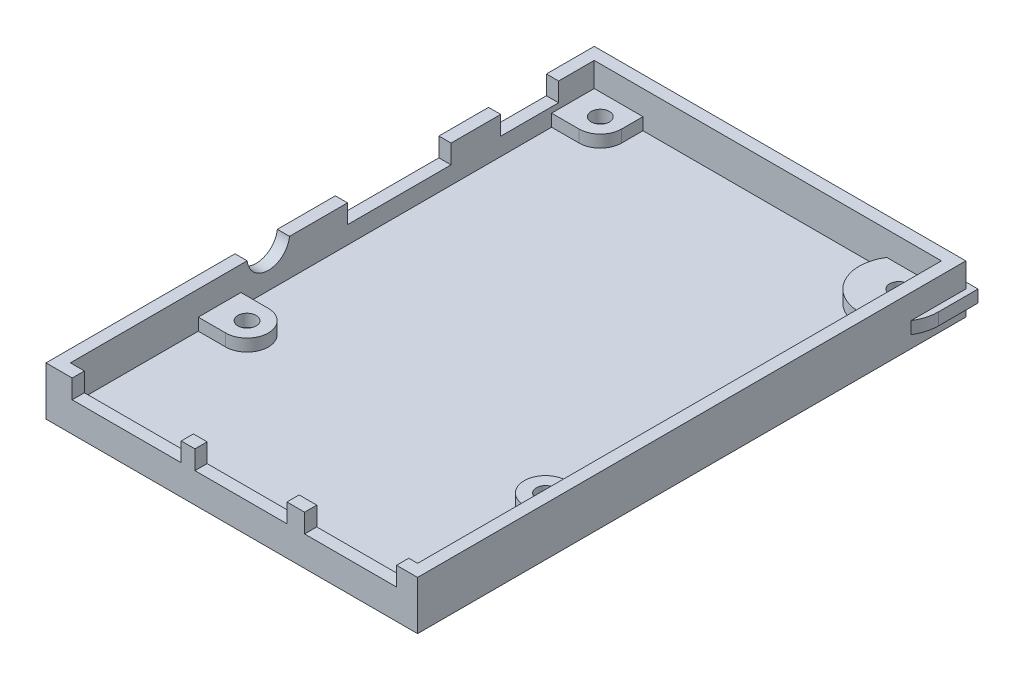
SolidWorks part; units mm, degrees
material "Acrylic (Medium-high impact)"
ref_plane "Front Plane" through (0, 0, 0) normal (0, 0, 1) x (1, 0, 0)
ref_plane "Top Plane" through (0, 0, 0) normal (0, 1, 0) x (1, 0, 0)
ref_plane "Right Plane" through (0, 0, 0) normal (1, 0, 0) x (0, 0, -1)
sketch "Sketch1" plane through (0, 0, 0) normal (0, 1, 0) x (1, 0, 0)
  line L1 (-30.5, -45) -> (30.5, -45)
  line L2 (-30.5, -45) -> (-30.5, 45)
  line L3 (-30.5, 45) -> (30.5, 45)
  line L4 (30.5, -45) -> (30.5, 45)
  line L5 (-30.5, -45) -> (30.5, 45) construction
  line L6 (-30.5, 45) -> (30.5, -45) construction
  point P0 (0, 0)
  dimension "D1" = 90
  dimension "D2" = 61
extrude "Boss-Extrude1" add sketch "Sketch1" along normal blind 8
ref_plane "Plane1" through (0, 2, 0) normal (0, 1, 0) x (1, 0, 0)
sketch "Sketch4" plane through (0, 2, 0) normal (0, 1, 0) x (1, 0, 0)
  line L0 (30.5, -45) -> (30.5, 45) construction
  line L1 (-28.5, -43) -> (28.5, -43)
  line L2 (-28.5, -43) -> (-28.5, 43)
  line L3 (-28.5, 43) -> (28.5, 43)
  line L4 (28.5, -43) -> (28.5, 43)
  line L5 (-28.5, -43) -> (28.5, 43) construction
  line L6 (-28.5, 43) -> (28.5, -43) construction
  line L7 (30.5, 45) -> (-30.5, 45) construction
  point P0 (0, 0)
  dimension "D1" = 2
  dimension "D2" = 2
extrude "Cut-Extrude1" cut sketch "Sketch4" along normal up to surface (6 mm away) up to face at (0, 8, 0)
sketch "Sketch5" plane through (0, 2, 0) normal (0, 1, 0) x (1, 0, 0)
  line L0 (28.5, 43) -> (28.5, -43) construction
  line L1 (25, -15) -> (28.5, -15)
  line L2 (-28.5, 43) -> (28.5, 43) construction
  line L3 (28.5, -43) -> (28.5, 43) construction
  line L4 (25, -22) -> (28.5, -22)
  line L5 (28.5, -22) -> (28.5, -15)
  line L9 (31.5, 39.5) -> (31.5, 46)
  line L10 (31.5, 46) -> (25, 46)
  line L12 (28.5, 43) -> (-28.5, 43) construction
  line L13 (-20.5, 39.5) -> (-20.5, 43)
  line L15 (-24, 36) -> (-28.5, 36)
  line L16 (-28.5, 43) -> (-28.5, -43) construction
  line L17 (-28.5, 36) -> (-28.5, 43)
  line L18 (-20.5, 43) -> (-28.5, 43)
  line L19 (-24, -15) -> (-28.5065, -15)
  line L22 (-28.5065, -15) -> (-28.5, -22)
  line L23 (-28.5, -43) -> (-28.5, 43) construction
  line L24 (-28.5, -22) -> (-24, -22)
  circle A0 centre (25, 39.5) radius 1.5
  circle A1 centre (-24, 39.5) radius 1.5
  circle A2 centre (25, -18.5) radius 1.5
  circle A3 centre (-24, -18.5) radius 1.5
  arc A4 (-24, -22) -> (-24, -15) centre (-24, -18.5) ccw
  arc A5 (25, -15) -> (25, -22) centre (25, -18.5) ccw
  arc A6 (25, 46) -> (31.5, 39.5) centre (25, 39.5) ccw
  arc A7 (-24, 36) -> (-20.5, 39.5) centre (-24, 39.5) ccw
  point P4 (-28.5, -14.7585)
  dimension "D1" = 3
  dimension "D5" = 3
  dimension "D7" = 3
  dimension "D8" = 7
  dimension "D9" = 7
  dimension "D2" = 49
  dimension "D3" = 3.5
  dimension "D4" = 3.5
  dimension "D6" = 58
extrude "Boss-Extrude12" add sketch "Sketch5" along normal blind 2
sketch "Sketch6" plane through (-30.5, 0, 0) normal (-1, 0, 0) x (0, 0, 1)
  line L0 (15, 4) -> (22, 4) construction
  line L1 (-43, 8) -> (-43, 4) construction
  line L3 (-19.5, 4.9) -> (-2.5, 4.9)
  line L4 (-19.5, 4.9) -> (-19.5, 11.4)
  line L5 (-19.5, 11.4) -> (-2.5, 11.4)
  line L6 (-2.5, 4.9) -> (-2.5, 11.4)
  line L7 (-19.5, 4.9) -> (-2.5, 11.4) construction
  line L8 (-19.5, 11.4) -> (-2.5, 4.9) construction
  line L10 (-37.15, 4.9) -> (-27.65, 4.9)
  line L11 (-37.15, 4.9) -> (-37.15, 8.9)
  line L12 (-37.15, 8.9) -> (-27.65, 8.9)
  line L13 (-27.65, 4.9) -> (-27.65, 8.9)
  line L14 (-37.15, 4.9) -> (-27.65, 8.9) construction
  line L15 (-37.15, 8.9) -> (-27.65, 4.9) construction
  circle A0 centre (10.5, 8.4) radius 3.5
  point P2 (0, 0)
  point P6 (-11, 8.15)
  point P11 (0, 0)
  point P12 (-19.5, 10.4247)
  point P13 (-32.4, 6.9)
  point P18 (0, 0)
  point P19 (0, 0)
  dimension "D1" = 7
  dimension "D2" = 4.4
  dimension "D3" = 53.5
  dimension "D4" = 17
  dimension "D5" = 9.5
  dimension "D6" = 10.6
  dimension "D7" = 32
  dimension "D9" = 6.5
  dimension "D10" = 4
extrude "Cut-Extrude2" cut sketch "Sketch6" against normal up to next
sketch "Sketch8" plane through (0, 0, 45) normal (0, 0, 1) x (1, 0, 0)
  line L0 (-28.5, 4) -> (-24, 4) construction
  line L1 (-26.2, 20.4) -> (-8.3, 20.4)
  line L2 (-26.2, 20.4) -> (-26.2, 4.9)
  line L3 (-26.2, 4.9) -> (-8.3, 4.9)
  line L4 (-8.3, 20.4) -> (-8.3, 4.9)
  line L5 (-26.2, 20.4) -> (-8.3, 4.9) construction
  line L6 (-26.2, 4.9) -> (-8.3, 20.4) construction
  line L7 (-6.05, 20.9) -> (9.05, 20.9)
  line L8 (-6.05, 20.9) -> (-6.05, 4.9)
  line L9 (-6.05, 4.9) -> (9.05, 4.9)
  line L10 (9.05, 20.9) -> (9.05, 4.9)
  line L11 (-6.05, 20.9) -> (9.05, 4.9) construction
  line L12 (-6.05, 4.9) -> (9.05, 20.9) construction
  line L13 (11.95, 20.9) -> (27.05, 20.9)
  line L14 (11.95, 20.9) -> (11.95, 4.9)
  line L15 (11.95, 4.9) -> (27.05, 4.9)
  line L16 (27.05, 20.9) -> (27.05, 4.9)
  line L17 (11.95, 20.9) -> (27.05, 4.9) construction
  line L18 (11.95, 4.9) -> (27.05, 20.9) construction
  line L20 (-28.5, 8) -> (-28.5, 2) construction
  point P0 (-17.25, 12.65)
  point P5 (1.5, 12.9)
  point P10 (19.5, 12.9)
  dimension "D1" = 0.9
  dimension "D2" = 15.5
  dimension "D3" = 16
  dimension "D4" = 17.9
  dimension "D5" = 15.1
  dimension "D6" = 11.25
  dimension "D7" = 30
  dimension "D8" = 48
extrude "Cut-Extrude3" cut sketch "Sketch8" against normal up to next
